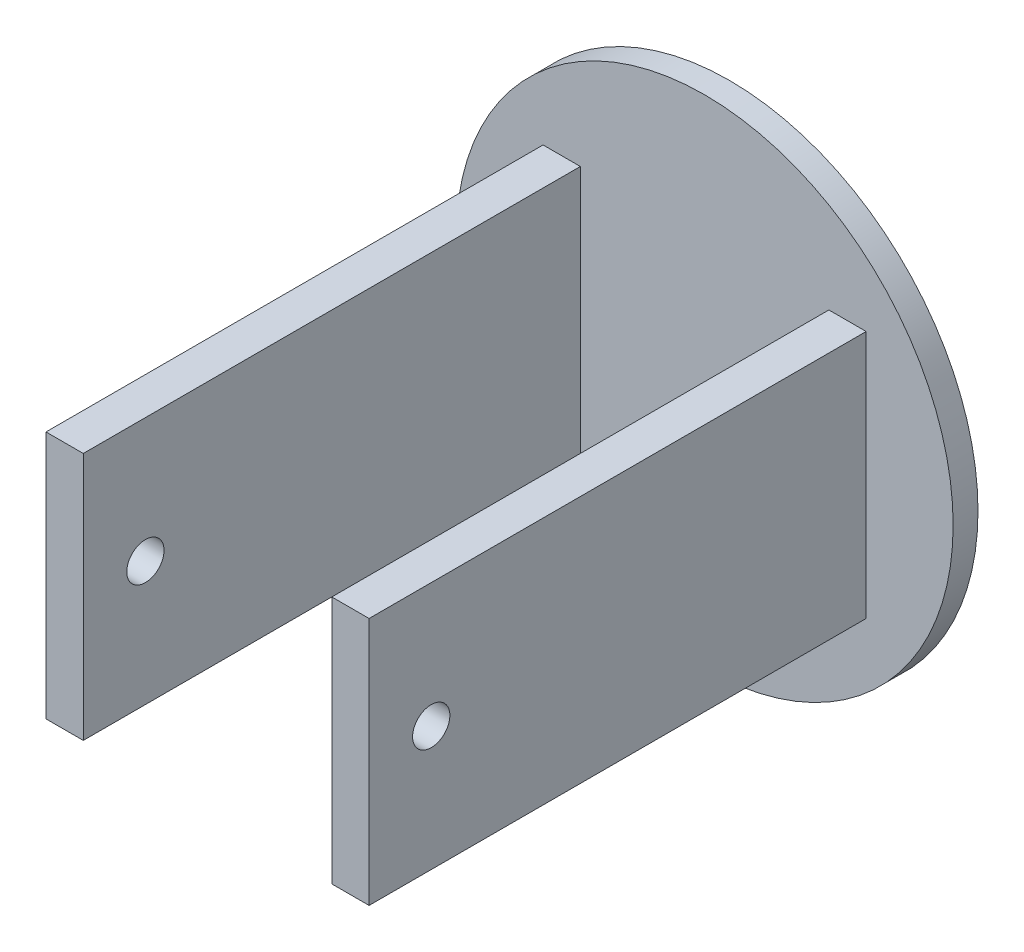
SolidWorks part; units mm, degrees
ref_plane "Front Plane" through (0, 0, 0) normal (0, 0, 1) x (1, 0, 0)
ref_plane "Top Plane" through (0, 0, 0) normal (0, 1, 0) x (1, 0, 0)
ref_plane "Right Plane" through (0, 0, 0) normal (1, 0, 0) x (0, 0, -1)
sketch "Sketch1" plane through (0, 0, 0) normal (0, 0, 1) x (1, 0, 0)
  circle A0 centre (0, 0) radius 20
  dimension "D1" = 40
extrude "Boss-Extrude1" add sketch "Sketch1" along normal blind 2
sketch "Sketch2" plane through (0, 0, 0) normal (0, 0, -1) x (-1, 0, 0)
  circle A0 centre (0, 0) radius 2
  dimension "D1" = 4
extrude "Boss-Extrude2" add sketch "Sketch2" along normal blind 1
sketch "Sketch3" plane through (0, 0, 2) normal (0, 0, 1) x (1, 0, 0)
  line L1 (-13, 10) -> (-10, 10)
  line L2 (-13, 10) -> (-13, -10)
  line L3 (-13, -10) -> (-10, -10)
  line L4 (-10, 10) -> (-10, -10)
  dimension "D1" = 20
  dimension "D2" = 10
  dimension "D3" = 10
  dimension "D4" = 3
extrude "Boss-Extrude3" add sketch "Sketch3" along normal blind 40
mirror "Mirror1" about plane through (0, 0, 0) normal (1, 0, 0) of "Boss-Extrude3"
sketch "Sketch5" plane through (-13, 0, 0) normal (-1, 0, 0) x (0, 0, 1)
  line L0 (42, 10) -> (2, 10) construction
  line L1 (42, 10) -> (42, -10) construction
  circle A0 centre (37, 0) radius 1.5
  dimension "D1" = 3
  dimension "D2" = 10
  dimension "D3" = 5
extrude "Cut-Extrude1" cut sketch "Sketch5" against normal through all
